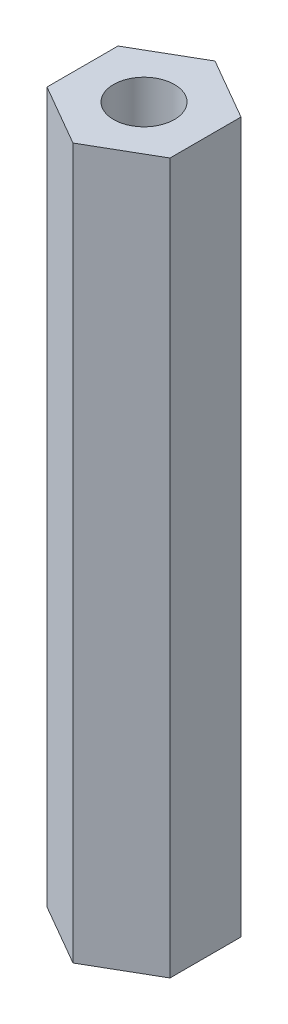
SolidWorks part; units mm, degrees
ref_plane "前视基准面" through (0, 0, 0) normal (0, 0, 1) x (1, 0, 0)
ref_plane "上视基准面" through (0, 0, 0) normal (0, 1, 0) x (1, 0, 0)
ref_plane "右视基准面" through (0, 0, 0) normal (1, 0, 0) x (0, 0, -1)
other "Configuration Table"
sketch "草图1" plane through (0, 0, 0) normal (0, 1, 0) x (1, 0, 0)
  line L0 (0, 0) -> (0, 3.5)
  line L2 (0, 3.5) -> (-3.0311, 1.75)
  line L3 (-3.0311, 1.75) -> (-3.0311, -1.75)
  line L4 (-3.0311, -1.75) -> (0, -3.5)
  line L5 (0, -3.5) -> (3.0311, -1.75)
  line L6 (3.0311, -1.75) -> (3.0311, 1.75)
  line L7 (3.0311, 1.75) -> (0, 3.5)
  circle A0 centre (0, 0) radius 1.5
  circle A1 centre (0, 0) radius 3.0311 construction
extrude "凸台-拉伸1" add sketch "草图1" along normal blind 35
